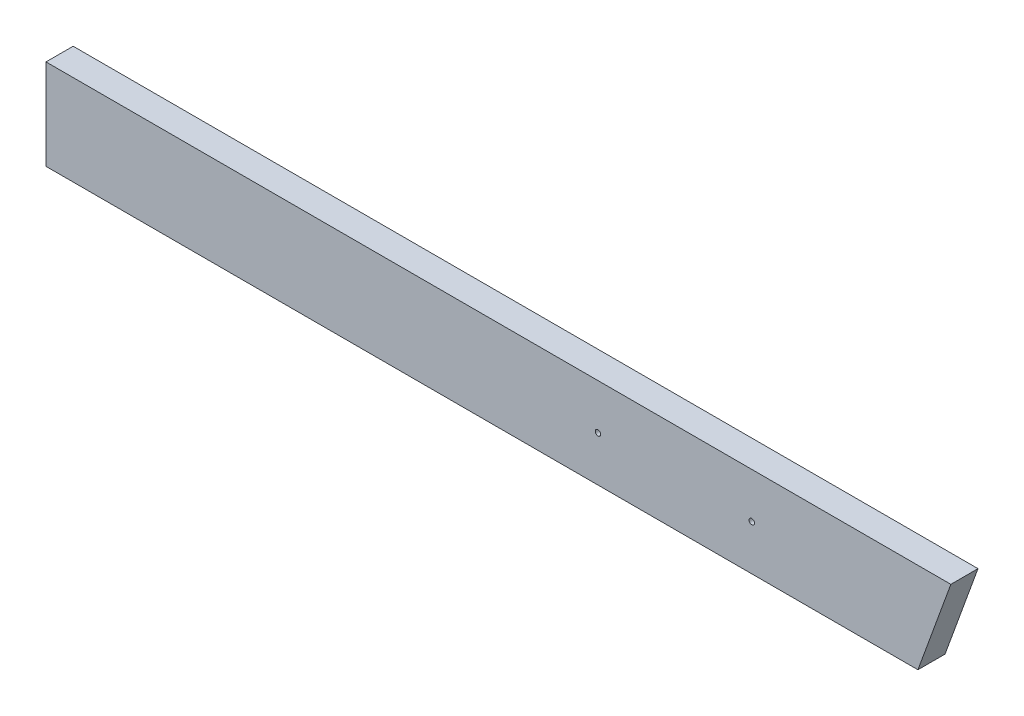
SolidWorks part; units mm, degrees
material "Pine"
ref_plane "Front Plane" through (0, 0, 0) normal (0, 0, 1) x (1, 0, 0)
ref_plane "Top Plane" through (0, 0, 0) normal (0, 1, 0) x (1, 0, 0)
ref_plane "Right Plane" through (0, 0, 0) normal (1, 0, 0) x (0, 0, -1)
sketch "Sketch1" plane through (0, 0, 0) normal (0, 0, 1) x (1, 0, 0)
  line L0 (500, 50) -> (463.603, -50)
  line L1 (-500, 50) -> (500, 50)
  line L2 (-500, 50) -> (-500, -50)
  line L3 (-500, -50) -> (500, -50) construction
  line L4 (500, 50) -> (500, -50) construction
  line L5 (-500, 50) -> (500, -50) construction
  line L6 (-500, -50) -> (500, 50) construction
  line L7 (463.603, -50) -> (-500, -50)
  point P0 (0, 0)
  dimension "D1" = 100
  dimension "D2" = 1000
  dimension "D3" = 110
extrude "Boss-Extrude1" add sketch "Sketch1" along normal blind 30
sketch "Sketch3" plane through (0, 0, 30) normal (0, 0, 1) x (1, 0, 0)
  circle A0 centre (110, 0) radius 3
  circle A1 centre (280, 0) radius 3
  dimension "D3" = 6
  dimension "D1" = 110
  dimension "D2" = 280
extrude "Cut-Extrude2" cut sketch "Sketch3" against normal through all
